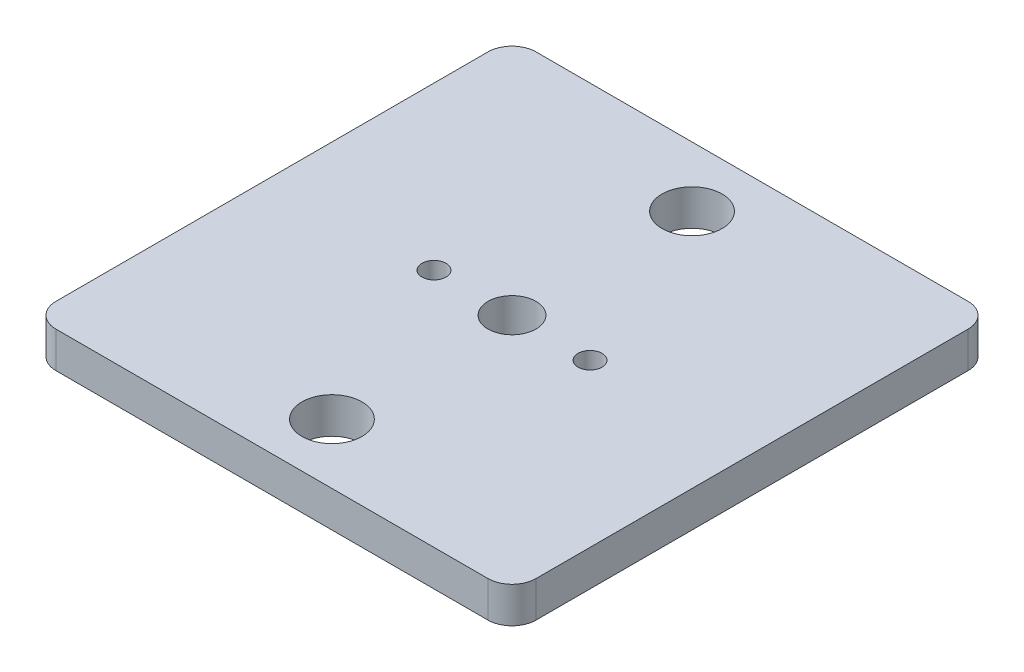
SolidWorks part; units mm, degrees
ref_plane "Front Plane" through (0, 0, 0) normal (0, 0, 1) x (1, 0, 0)
ref_plane "Top Plane" through (0, 0, 0) normal (0, 1, 0) x (1, 0, 0)
ref_plane "Right Plane" through (0, 0, 0) normal (1, 0, 0) x (0, 0, -1)
sketch "Sketch2" plane through (0, 0, 0) normal (0, 1, 0) x (1, 0, 0)
  line L1 (-18, -20) -> (18, -20)
  line L2 (-20, -18) -> (-20, 18)
  line L3 (-18, 20) -> (18, 20)
  line L4 (20, -18) -> (20, 18)
  line L5 (-20, -20) -> (20, 20) construction
  line L6 (-20, 20) -> (20, -20) construction
  arc A1 (-18, -20) -> (-20, -18) centre (-18, -18) cw
  arc A2 (18, -20) -> (20, -18) centre (18, -18) ccw
  arc A3 (18, 20) -> (20, 18) centre (18, 18) cw
  arc A4 (-20, 18) -> (-18, 20) centre (-18, 18) cw
  point P0 (0, 0)
  dimension "D3" = 2
  dimension "D1" = 40
  dimension "D2" = 40
sketch "Sketch3" plane through (0, 0, 0) normal (0, 1, 0) x (1, 0, 0)
  line L0 (-20, -20) -> (20, 20) construction
  circle A0 centre (0, 0) radius 2
  circle A1 centre (0, 15) radius 2.5
  circle A2 centre (0, -15) radius 2.5
  point P8 (0, 0)
  dimension "D1" = 4
  dimension "D2" = 5
  dimension "D3" = 5
  dimension "D4" = 15
  dimension "D5" = 15
sketch "Sketch4" plane through (0, 0, 0) normal (0, 1, 0) x (1, 0, 0)
  circle A0 centre (6.5, 0) radius 1
  circle A1 centre (-6.5, 0) radius 1
  point P4 (0, 0)
  dimension "D1" = 2
  dimension "D2" = 2
  dimension "D3" = 6.5
  dimension "D4" = 6.5
extrude "Boss-Extrude1" add sketch "Sketch2" along normal blind 3
extrude "Cut-Extrude3" cut sketch "Sketch3" along normal through all
extrude "Cut-Extrude4" cut sketch "Sketch4" along normal blind 3
